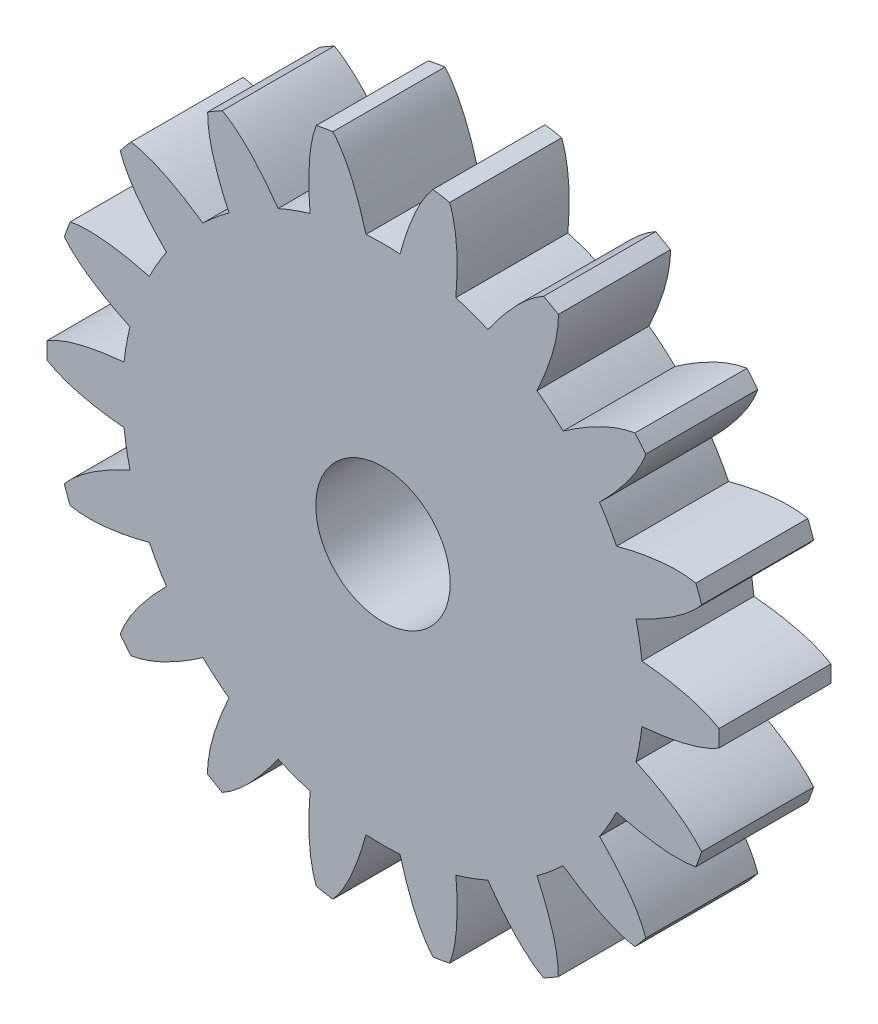
SolidWorks part; units mm, degrees
ref_plane "Front Plane" through (0, 0, 0) normal (0, 0, 1) x (1, 0, 0)
ref_plane "Top Plane" through (0, 0, 0) normal (0, 1, 0) x (1, 0, 0)
ref_plane "Right Plane" through (0, 0, 0) normal (1, 0, 0) x (0, 0, -1)
sketch "Sketch2" plane through (0, 0, 0) normal (0, 0, 1) x (1, 0, 0)
  line L0 (-2.6047, 14.7721) -> (-2.0185, 11.4474) construction
  arc A0 (-3.253, 11.1595) -> (-4.6813, 10.6397) centre (0, 0) ccw
  arc A1 (-2.2327, 14.8329) -> (-2.9751, 14.702) centre (0, 0) ccw
  arc A2 (2.9751, 14.702) -> (2.2327, 14.8329) centre (0, 0) ccw
  arc A3 (7.8241, 12.7978) -> (7.1712, 13.1748) centre (0, 0) ccw
  arc A4 (11.7293, 9.35) -> (11.2447, 9.9275) centre (0, 0) ccw
  arc A5 (14.2199, 4.7745) -> (13.962, 5.4829) centre (0, 0) ccw
  arc A6 (14.9953, -0.377) -> (14.9953, 0.377) centre (0, 0) ccw
  arc A7 (13.962, -5.4829) -> (14.2199, -4.7745) centre (0, 0) ccw
  arc A8 (11.2447, -9.9275) -> (11.7293, -9.35) centre (0, 0) ccw
  arc A9 (7.1712, -13.1748) -> (7.8241, -12.7978) centre (0, 0) ccw
  arc A10 (2.2327, -14.8329) -> (2.9751, -14.702) centre (0, 0) ccw
  arc A11 (-2.9751, -14.702) -> (-2.2327, -14.8329) centre (0, 0) ccw
  arc A12 (-7.8241, -12.7978) -> (-7.1712, -13.1748) centre (0, 0) ccw
  arc A13 (-11.7293, -9.35) -> (-11.2447, -9.9275) centre (0, 0) ccw
  arc A14 (-14.2199, -4.7745) -> (-13.962, -5.4829) centre (0, 0) ccw
  arc A15 (-14.9953, 0.377) -> (-14.9953, -0.377) centre (0, 0) ccw
  arc A16 (-13.962, 5.4829) -> (-14.2199, 4.7745) centre (0, 0) ccw
  arc A17 (-11.2447, 9.9275) -> (-11.7293, 9.35) centre (0, 0) ccw
  arc A18 (-7.1712, 13.1748) -> (-7.8241, 12.7978) centre (0, 0) ccw
  arc A19 (-6.8736, 9.374) -> (-8.038, 8.3969) centre (0, 0) ccw
  arc A20 (-9.6652, 6.4577) -> (-10.4251, 5.1414) centre (0, 0) ccw
  arc A21 (-11.2909, 2.7626) -> (-11.5549, 1.2657) centre (0, 0) ccw
  arc A22 (-11.5549, -1.2657) -> (-11.2909, -2.7626) centre (0, 0) ccw
  arc A23 (-10.4251, -5.1414) -> (-9.6652, -6.4577) centre (0, 0) ccw
  arc A24 (-8.038, -8.3969) -> (-6.8736, -9.374) centre (0, 0) ccw
  arc A25 (-4.6813, -10.6397) -> (-3.253, -11.1595) centre (0, 0) ccw
  arc A26 (-0.76, -11.5991) -> (0.76, -11.5991) centre (0, 0) ccw
  arc A27 (3.253, -11.1595) -> (4.6813, -10.6397) centre (0, 0) ccw
  arc A28 (6.8736, -9.374) -> (8.038, -8.3969) centre (0, 0) ccw
  arc A29 (9.6652, -6.4577) -> (10.4251, -5.1414) centre (0, 0) ccw
  arc A30 (11.2909, -2.7626) -> (11.5549, -1.2657) centre (0, 0) ccw
  arc A31 (11.5549, 1.2657) -> (11.2909, 2.7626) centre (0, 0) ccw
  arc A32 (10.4251, 5.1414) -> (9.6652, 6.4577) centre (0, 0) ccw
  arc A33 (8.038, 8.3969) -> (6.8736, 9.374) centre (0, 0) ccw
  arc A34 (4.6813, 10.6397) -> (3.253, 11.1595) centre (0, 0) ccw
  arc A35 (0.76, 11.5991) -> (-0.76, 11.5991) centre (0, 0) ccw
  circle A36 centre (0, 0) radius 3
  spline S0 degree 2 poles (-2.9751, 14.702) (-3.4475, 13.4911) (-3.253, 11.1595) knots 0 0 0 0.715421 0.715421 0.715421
  spline S1 degree 2 poles (-2.2327, 14.8329) (-1.3746, 13.8566) (-0.76, 11.5991) knots 0 0 0 0.715421 0.715421 0.715421
  spline S2 degree 2 poles (2.2327, 14.8329) (1.3746, 13.8566) (0.76, 11.5991) knots 0 0 0 0.715421 0.715421 0.715421
  spline S3 degree 2 poles (2.9751, 14.702) (3.4475, 13.4911) (3.253, 11.1595) knots 0 0 0 0.715421 0.715421 0.715421
  spline S4 degree 2 poles (7.1712, 13.1748) (6.031, 12.5508) (4.6813, 10.6397) knots 0 0 0 0.715421 0.715421 0.715421
  spline S5 degree 2 poles (7.8241, 12.7978) (7.8538, 11.4984) (6.8736, 9.374) knots 0 0 0 0.715421 0.715421 0.715421
  spline S6 degree 2 poles (11.2447, 9.9275) (9.9599, 9.7312) (8.038, 8.3969) knots 0 0 0 0.715421 0.715421 0.715421
  spline S7 degree 2 poles (11.7293, 9.35) (11.3129, 8.1188) (9.6652, 6.4577) knots 0 0 0 0.715421 0.715421 0.715421
  spline S8 degree 2 poles (13.962, 5.4829) (12.6875, 5.7378) (10.4251, 5.1414) knots 0 0 0 0.715421 0.715421 0.715421
  spline S9 degree 2 poles (14.2199, 4.7745) (13.4074, 3.7599) (11.2909, 2.7626) knots 0 0 0 0.715421 0.715421 0.715421
  spline S10 degree 2 poles (14.9953, 0.377) (13.8848, 1.0524) (11.5549, 1.2657) knots 0 0 0 0.715421 0.715421 0.715421
  spline S11 degree 2 poles (14.9953, -0.377) (13.8848, -1.0524) (11.5549, -1.2657) knots 0 0 0 0.715421 0.715421 0.715421
  spline S12 degree 2 poles (14.2199, -4.7745) (13.4074, -3.7599) (11.2909, -2.7626) knots 0 0 0 0.715421 0.715421 0.715421
  spline S13 degree 2 poles (13.962, -5.4829) (12.6875, -5.7378) (10.4251, -5.1414) knots 0 0 0 0.715421 0.715421 0.715421
  spline S14 degree 2 poles (11.7293, -9.35) (11.3129, -8.1188) (9.6652, -6.4577) knots 0 0 0 0.715421 0.715421 0.715421
  spline S15 degree 2 poles (11.2447, -9.9275) (9.9599, -9.7312) (8.038, -8.3969) knots 0 0 0 0.715421 0.715421 0.715421
  spline S16 degree 2 poles (7.8241, -12.7978) (7.8538, -11.4984) (6.8736, -9.374) knots 0 0 0 0.715421 0.715421 0.715421
  spline S17 degree 2 poles (7.1712, -13.1748) (6.031, -12.5508) (4.6813, -10.6397) knots 0 0 0 0.715421 0.715421 0.715421
  spline S18 degree 2 poles (2.9751, -14.702) (3.4475, -13.4911) (3.253, -11.1595) knots 0 0 0 0.715421 0.715421 0.715421
  spline S19 degree 2 poles (2.2327, -14.8329) (1.3746, -13.8566) (0.76, -11.5991) knots 0 0 0 0.715421 0.715421 0.715421
  spline S20 degree 2 poles (-2.2327, -14.8329) (-1.3746, -13.8566) (-0.76, -11.5991) knots 0 0 0 0.715421 0.715421 0.715421
  spline S21 degree 2 poles (-2.9751, -14.702) (-3.4475, -13.4911) (-3.253, -11.1595) knots 0 0 0 0.715421 0.715421 0.715421
  spline S22 degree 2 poles (-7.1712, -13.1748) (-6.031, -12.5508) (-4.6813, -10.6397) knots 0 0 0 0.715421 0.715421 0.715421
  spline S23 degree 2 poles (-7.8241, -12.7978) (-7.8538, -11.4984) (-6.8736, -9.374) knots 0 0 0 0.715421 0.715421 0.715421
  spline S24 degree 2 poles (-11.2447, -9.9275) (-9.9599, -9.7312) (-8.038, -8.3969) knots 0 0 0 0.715421 0.715421 0.715421
  spline S25 degree 2 poles (-11.7293, -9.35) (-11.3129, -8.1188) (-9.6652, -6.4577) knots 0 0 0 0.715421 0.715421 0.715421
  spline S26 degree 2 poles (-13.962, -5.4829) (-12.6875, -5.7378) (-10.4251, -5.1414) knots 0 0 0 0.715421 0.715421 0.715421
  spline S27 degree 2 poles (-14.2199, -4.7745) (-13.4074, -3.7599) (-11.2909, -2.7626) knots 0 0 0 0.715421 0.715421 0.715421
  spline S28 degree 2 poles (-14.9953, -0.377) (-13.8848, -1.0524) (-11.5549, -1.2657) knots 0 0 0 0.715421 0.715421 0.715421
  spline S29 degree 2 poles (-14.9953, 0.377) (-13.8848, 1.0524) (-11.5549, 1.2657) knots 0 0 0 0.715421 0.715421 0.715421
  spline S30 degree 2 poles (-14.2199, 4.7745) (-13.4074, 3.7599) (-11.2909, 2.7626) knots 0 0 0 0.715421 0.715421 0.715421
  spline S31 degree 2 poles (-13.962, 5.4829) (-12.6875, 5.7378) (-10.4251, 5.1414) knots 0 0 0 0.715421 0.715421 0.715421
  spline S32 degree 2 poles (-11.7293, 9.35) (-11.3129, 8.1188) (-9.6652, 6.4577) knots 0 0 0 0.715421 0.715421 0.715421
  spline S33 degree 2 poles (-11.2447, 9.9275) (-9.9599, 9.7312) (-8.038, 8.3969) knots 0 0 0 0.715421 0.715421 0.715421
  spline S34 degree 2 poles (-7.8241, 12.7978) (-7.8538, 11.4984) (-6.8736, 9.374) knots 0 0 0 0.715421 0.715421 0.715421
  spline S35 degree 2 poles (-7.1712, 13.1748) (-6.031, 12.5508) (-4.6813, 10.6397) knots 0 0 0 0.715421 0.715421 0.715421
  dimension "D1" = 6
extrude "Boss-Extrude1" add sketch "Sketch2" along normal blind 5
